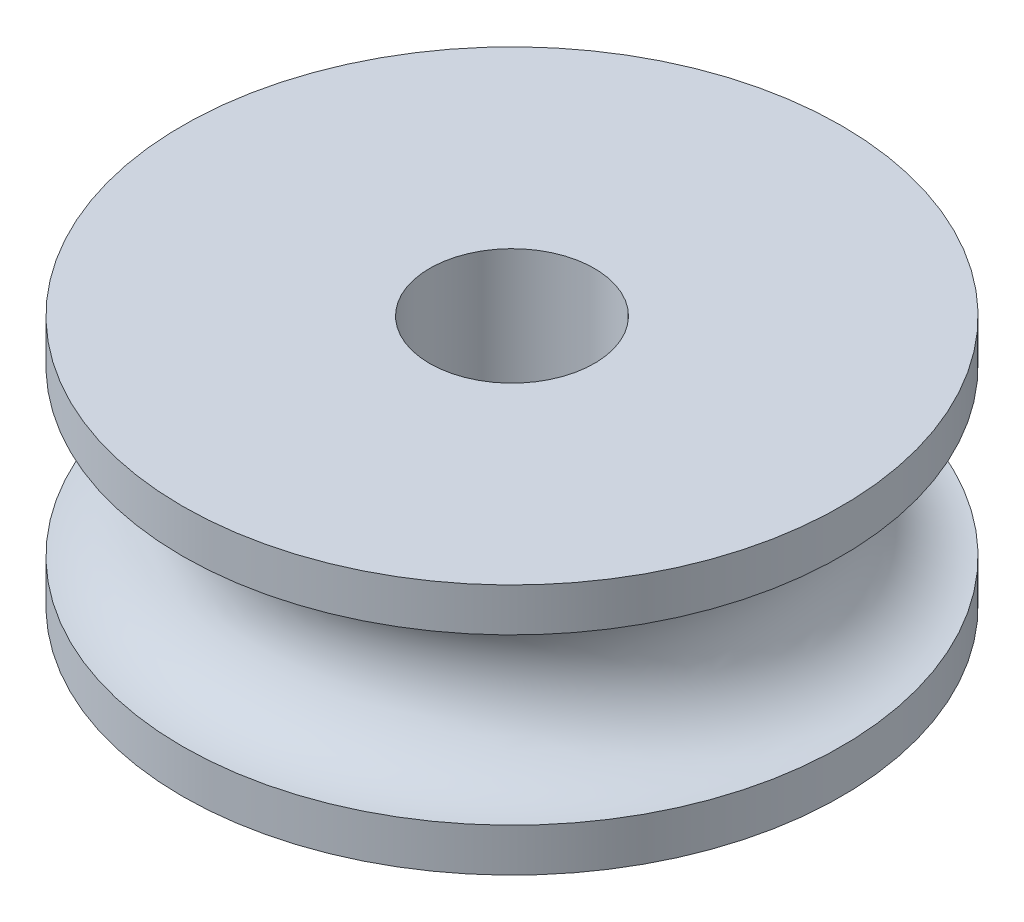
SolidWorks part; units mm, degrees
ref_plane "Alzado" through (0, 0, 0) normal (0, 0, 1) x (1, 0, 0)
ref_plane "Planta" through (0, 0, 0) normal (0, 1, 0) x (1, 0, 0)
ref_plane "Vista lateral" through (0, 0, 0) normal (1, 0, 0) x (0, 0, -1)
sketch "Croquis1" plane through (0, 0, 0) normal (0, 0, 1) x (1, 0, 0)
  line L0 (0, 14.525) -> (-38.1, 14.525)
  line L1 (-38.1, 14.525) -> (-38.1, 9.525)
  line L2 (0, 0) -> (-28.575, 0)
  line L3 (0, 62.4336) -> (0, -43.083) construction
  line L4 (0, 14.525) -> (0, -14.525)
  line L5 (58.914, 0) -> (-101.0039, 0) construction
  line L6 (0, -14.525) -> (-38.1, -14.525)
  line L7 (-38.1, -14.525) -> (-38.1, -9.525)
  arc A0 (-38.1, 9.525) -> (-38.1, -9.525) centre (-38.1, 0) cw
  point P11 (35.7768, -3.645)
  point P12 (-101.0039, 0)
  dimension "D1" = 9.525
  dimension "D2" = 5
  dimension "D3" = 38.1
revolve "Revolución1" add sketch "Croquis1" angle 360 about L3
sketch "Croquis2" plane through (0, 14.525, 0) normal (0, 1, 0) x (1, 0, 0)
  circle A0 centre (0, 0) radius 9.525
  dimension "D1" = 19.05
extrude "Cortar-Extruir1" cut sketch "Croquis2" against normal blind 40
